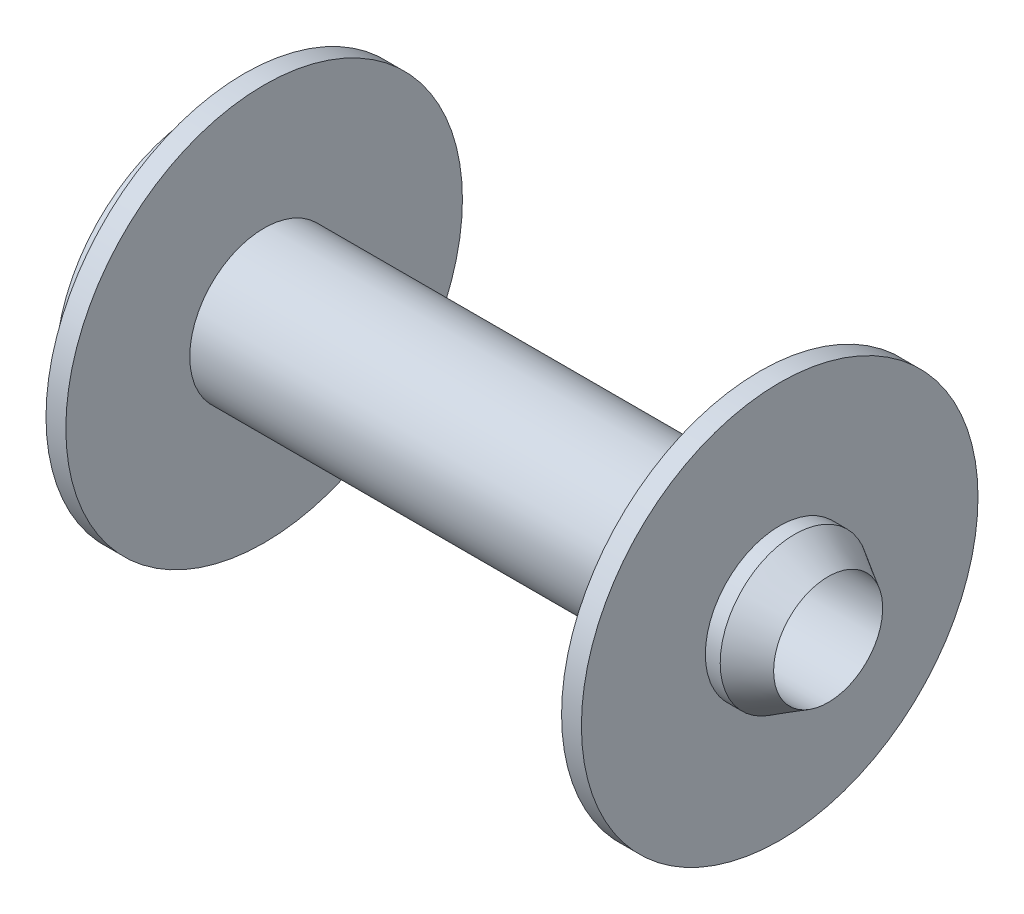
SolidWorks part; units mm, degrees
ref_plane "Front Plane" through (0, 0, 0) normal (0, 0, 1) x (1, 0, 0)
ref_plane "Top Plane" through (0, 0, 0) normal (0, 1, 0) x (1, 0, 0)
ref_plane "Right Plane" through (0, 0, 0) normal (1, 0, 0) x (0, 0, -1)
sketch "Sketch1" plane through (0, 0, 0) normal (0, 0, 1) x (1, 0, 0)
  line L0 (63.7726, 11) -> (57, 15)
  line L1 (54, 15) -> (54, 40)
  line L2 (54, 40) -> (50, 40)
  line L3 (50, 40) -> (50, 15)
  line L4 (54, 15) -> (57, 15)
  line L5 (50, 15) -> (-50, 15)
  line L6 (-50, 15) -> (-50, 40)
  line L7 (-50, 40) -> (-54, 40)
  line L8 (-54, 40) -> (-54, 15)
  line L9 (-54, 15) -> (-57, 15)
  line L10 (-57, 15) -> (-57, 30)
  line L11 (-57, 30) -> (-62, 30)
  line L12 (-62, 30) -> (-62, 15)
  line L13 (-62, 15) -> (-65.1079, 11)
  line L14 (-65.1079, 11) -> (63.7726, 11)
  line L15 (-22.2293, 0) -> (20.2885, 0) construction
  point P12 (0, 15)
  dimension "D1" = 4
  dimension "D2" = 3
  dimension "D3" = 3
  dimension "D4" = 100
  dimension "D5" = 5
  dimension "D6" = 15
  dimension "D7" = 25
  dimension "D8" = 15
  dimension "D9" = 11
revolve "Revolve1" add sketch "Sketch1" angle 360 about L15
